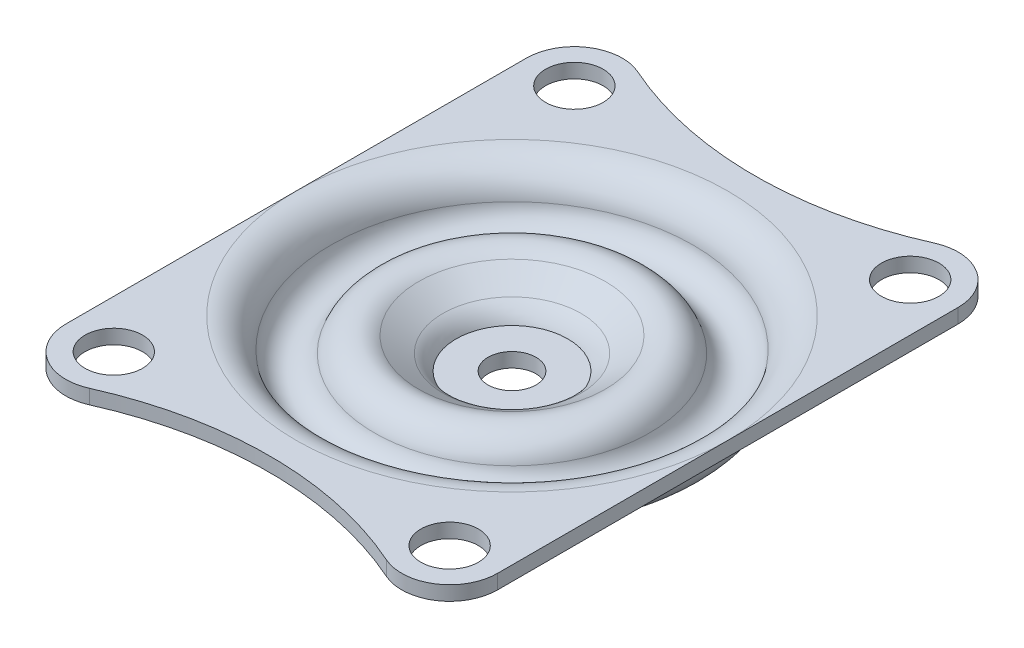
SolidWorks part; units mm, degrees
material "Cast Stainless Steel"
ref_plane "Front Plane" through (0, 0, 0) normal (0, 0, 1) x (1, 0, 0)
ref_plane "Top Plane" through (0, 0, 0) normal (0, 1, 0) x (1, 0, 0)
ref_plane "Right Plane" through (0, 0, 0) normal (1, 0, 0) x (0, 0, -1)
sketch "Sketch1" plane through (0, 0, 0) normal (0, 0, 1) x (1, 0, 0)
  line L0 (0, 0) -> (-7, 0)
  line L1 (-7, 0) -> (-16.5674, 0) construction
  line L2 (-8.0101, 1.845) -> (-10.5374, 3.4613)
  line L3 (-22.5, 5) -> (-68.5, 5)
  line L4 (0, 0) -> (0, 9.0938) construction
  arc A0 (-7, 0) -> (-8.0101, 1.845) centre (-9.19, 0) ccw
  arc A1 (-10.5374, 3.4613) -> (-12.9272, 2.6184) centre (-11.4034, 2.1072) ccw
  arc A2 (-12.9272, 2.6184) -> (-20.3515, 3.1892) centre (-16.5674, 3.8395) cw
  arc A3 (-20.3515, 3.1892) -> (-22.5, 5) centre (-22.5, 2.82) ccw
  dimension "D2" = 2.19
  dimension "D3" = 2.18
  dimension "D4" = 22.5
  dimension "D6" = 1.6073
  dimension "D7" = 3.8395
  dimension "D1" = 7
  dimension "D5" = 5
  dimension "D8" = 3
  dimension "D9" = 46
revolve "Revolve-Thin1" add sketch "Sketch1" angle 360 about L4
sketch "Sketch2" plane through (0, 6.5, 0) normal (0, 1, 0) x (1, 0, 0)
  line L0 (0, 0) -> (0, 63.2974) construction
  line L2 (-22.5, 24) -> (-22.5, -24)
  line L4 (22.5, 24) -> (22.5, -24)
  line L6 (-21.2161, -27.3452) -> (21.2161, 27.3452) construction
  line L7 (0, 0) -> (14.3493, 0) construction
  line L8 (-19.9566, 25.7219) -> (21.2161, -27.3452) construction
  circle A0 centre (-17.5, 24) radius 3
  circle A1 centre (0, 0) radius 14.3493 construction
  circle A2 centre (17.5, 24) radius 3
  circle A3 centre (17.5, -24) radius 3
  circle A4 centre (-17.5, -24) radius 3
  arc A5 (-15.466, 28.5676) -> (-22.5, 24) centre (-17.5, 24) ccw
  arc A6 (15.466, 28.5676) -> (22.5, 24) centre (17.5, 24) cw
  arc A7 (-15.466, -28.5676) -> (-22.5, -24) centre (-17.5, -24) cw
  arc A8 (15.466, -28.5676) -> (22.5, -24) centre (17.5, -24) ccw
  arc A9 (-15.466, 28.5676) -> (15.466, 28.5676) centre (0, 63.2974) ccw
  arc A10 (-15.466, -28.5676) -> (15.466, -28.5676) centre (0, -63.2974) cw
  circle A11 centre (-17.5, -24) radius 5 construction
  circle A12 centre (17.5, -24) radius 5 construction
  circle A13 centre (-17.5, 24) radius 5 construction
  circle A14 centre (17.5, 24) radius 5 construction
  point P0 (0, 0)
  dimension "D3" = 6
  dimension "D5" = 5
  dimension "D6" = 2
extrude "Cut-Extrude1" cut sketch "Sketch2" against normal blind 10 flip side to cut
sketch "Sketch3" plane through (0, 1.5, 0) normal (0, 1, 0) x (1, 0, 0)
  circle A0 centre (0, 0) radius 2.5
  dimension "D1" = 5
extrude "Cut-Extrude2" cut sketch "Sketch3" against normal up to next
